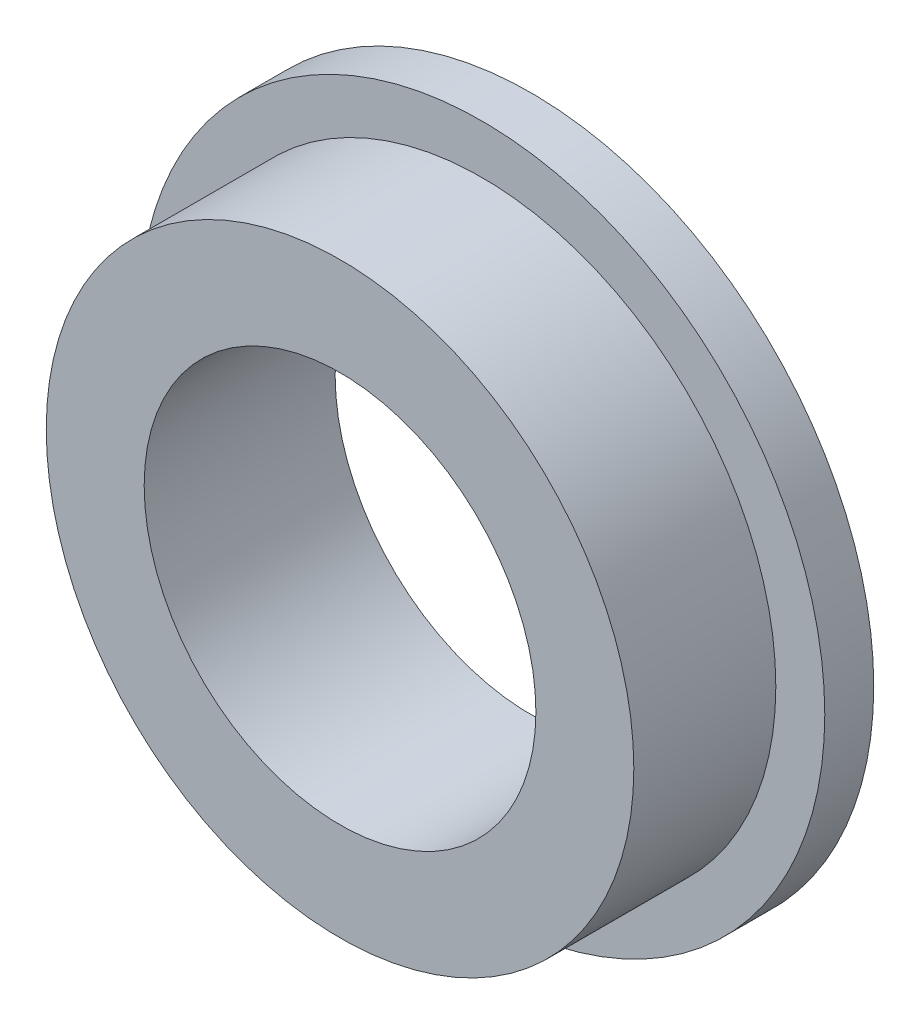
SolidWorks part; units mm, degrees
ref_plane "正面" through (0, 0, 0) normal (0, 0, 1) x (1, 0, 0)
ref_plane "平面" through (0, 0, 0) normal (0, 1, 0) x (1, 0, 0)
ref_plane "右側面" through (0, 0, 0) normal (1, 0, 0) x (0, 0, -1)
sketch "ｽｹｯﾁ2" plane through (0, 0, 0) normal (0, 0, 1) x (1, 0, 0)
  circle A0 centre (0, 0) radius 7
  circle A1 centre (0, 0) radius 4
  dimension "D1" = 14
  dimension "D2" = 8
extrude "ﾎﾞｽ - 押し出し1" add sketch "ｽｹｯﾁ2" along normal blind 1
sketch "ｽｹｯﾁ3" plane through (0, 0, 1) normal (0, 0, 1) x (1, 0, 0)
  circle A0 centre (0, 0) radius 4
  circle A1 centre (0, 0) radius 6
  dimension "D1" = 12
  dimension "D2" = 8
extrude "ﾎﾞｽ - 押し出し2" add sketch "ｽｹｯﾁ3" along normal blind 2.9
